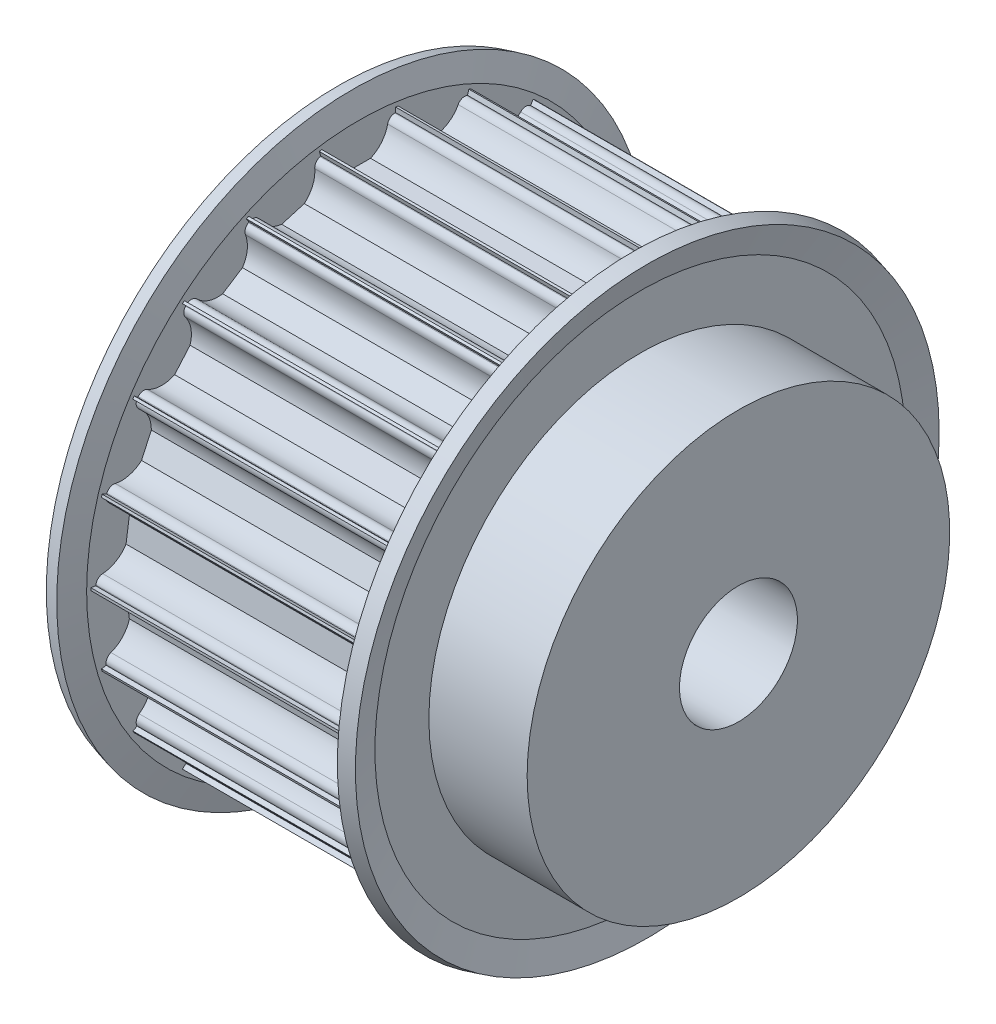
SolidWorks part; units mm, degrees
ref_plane "Front Plane" through (0, 0, 0) normal (0, 0, 1) x (1, 0, 0)
ref_plane "Top Plane" through (0, 0, 0) normal (0, 1, 0) x (1, 0, 0)
ref_plane "Right Plane" through (0, 0, 0) normal (1, 0, 0) x (0, 0, -1)
sketch "Sketch2" plane through (0, 0, 0) normal (0, 0, 1) x (1, 0, 0)
  line L0 (0, 0) -> (15.1167, 0) construction
  line L1 (0, 6) -> (0, 27.25)
  line L2 (0, 27.25) -> (30, 27.25)
  line L3 (30, 27.25) -> (30, 21.5)
  line L4 (30, 21.5) -> (40, 21.5)
  line L5 (40, 21.5) -> (40, 6)
  line L6 (40, 6) -> (0, 6)
  dimension "D1" = 6
  dimension "D2" = 27.25
  dimension "D3" = 30
  dimension "D4" = 10
  dimension "D5" = 15.5
revolve "Revolve1" add sketch "Sketch2" angle 360 about L0
sketch "Sketch3" plane through (0, 0, 0) normal (-1, 0, 0) x (0, 0, 1)
  line L0 (-3.6742, 26.5) -> (-3.75, 26.5)
  line L1 (-3.75, 26.5) -> (-3.75, 28.5)
  line L2 (-3.75, 28.5) -> (3.75, 28.5)
  line L3 (3.75, 28.5) -> (3.75, 26.5)
  line L4 (3.75, 26.5) -> (3.6742, 26.5)
  line L5 (-1.199, 23.75) -> (1.199, 23.75)
  arc A0 (-2.9394, 25.9) -> (-1.199, 23.75) centre (0, 26.5) ccw
  arc A1 (-2.9394, 25.9) -> (-3.6742, 26.5) centre (-3.6742, 25.75) ccw
  arc A2 (2.9394, 25.9) -> (3.6742, 26.5) centre (3.6742, 25.75) cw
  arc A3 (1.199, 23.75) -> (2.9394, 25.9) centre (0, 26.5) ccw
  point P6 (0, 28.5)
  point P11 (-3, 26.5)
  point P14 (3, 26.5)
  dimension "D2" = 3
  dimension "D5" = 0.75
  dimension "D6" = 0.75
  dimension "D1" = 26.5
  dimension "D3" = 2
  dimension "D4" = 7.5
  dimension "D7" = 2.75
extrude "Cut-Extrude1" cut sketch "Sketch3" against normal through all
pattern_circular "CirPattern1" count 22 over 360 about axis through (0, 0, 0) along (1, 0, 0) of "Cut-Extrude1"
sketch "Sketch4" plane through (0, 0, 0) normal (0, 0, 1) x (1, 0, 0)
  line L0 (30, 21.5) -> (28.6347, 21.5)
  line L1 (28.6347, 21.5) -> (28.6347, 27.69)
  line L2 (28.6347, 27.69) -> (29.2778, 30.09)
  line L3 (29.2778, 30.09) -> (30.7267, 29.7018)
  line L4 (30.7267, 29.7018) -> (30, 26.9898)
  line L5 (30, 26.9898) -> (30, 21.5)
  line L6 (15, 26.9539) -> (15, -5.6808) construction
  line L7 (0, 26.9539) -> (30, 26.9539) construction
  line L8 (0, 21.5) -> (1.3653, 21.5)
  line L9 (0, 26.9898) -> (0, 21.5)
  line L10 (-0.7267, 29.7018) -> (0, 26.9898)
  line L11 (0.7222, 30.09) -> (-0.7267, 29.7018)
  line L12 (1.3653, 27.69) -> (0.7222, 30.09)
  line L13 (1.3653, 21.5) -> (1.3653, 27.69)
  line L14 (0, 0) -> (-20.6757, 0) construction
  dimension "D1" = 15
  dimension "D2" = 1.5
  dimension "D3" = 2.4
  dimension "D4" = 6.19
revolve "Revolve2" add sketch "Sketch4" angle 360 about L14
